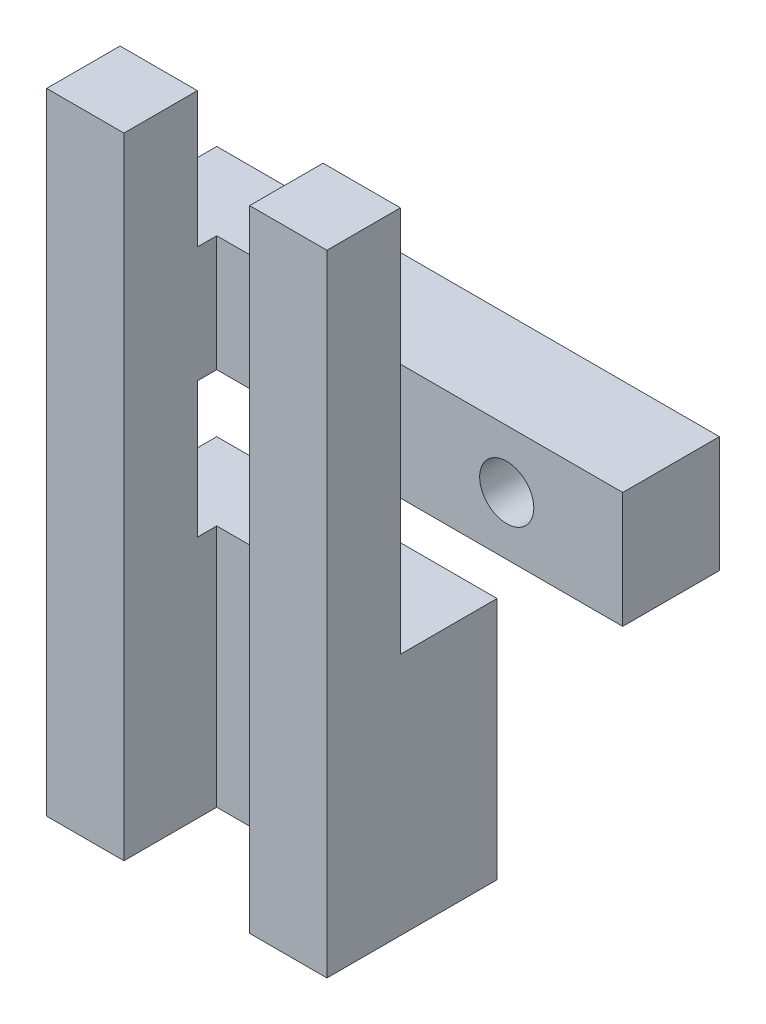
SolidWorks part; units mm, degrees
ref_plane "前视基准面" through (0, 0, 0) normal (0, 0, 1) x (1, 0, 0)
ref_plane "上视基准面" through (0, 0, 0) normal (0, 1, 0) x (1, 0, 0)
ref_plane "右视基准面" through (0, 0, 0) normal (1, 0, 0) x (0, 0, -1)
other "Configuration Table"
sketch "草图1" plane through (0, 0, 0) normal (0, 0, 1) x (1, 0, 0)
  line L1 (0, 0) -> (26, 0)
  line L2 (0, 0) -> (0, -6)
  line L3 (0, -6) -> (26, -6)
  line L4 (26, 0) -> (26, -6)
  circle A0 centre (20, -3) radius 1.4
  dimension "D5" = 2.8
  dimension "D1" = 26
  dimension "D2" = 6
  dimension "D3" = 3
  dimension "D4" = 6
extrude "凸台-拉伸1" add sketch "草图1" along normal blind 5
sketch "草图2" plane through (0, 0, 5) normal (0, 0, 1) x (1, 0, 0)
  line L0 (20, -3) -> (50020, -3) construction
  line L1 (-3.5767, 7) -> (49996.4233, 7) construction
  line L2 (0, 0) -> (0, -6) construction
  line L3 (0, 7) -> (4, 7)
  line L4 (0, 7) -> (0, -25.6)
  line L5 (0, -25.6) -> (4, -25.6)
  line L6 (4, 7) -> (4, -25.6)
  line L7 (10.5, 7) -> (14.5, 7)
  line L8 (10.5, 7) -> (10.5, -25.6)
  line L9 (10.5, -25.6) -> (14.5, -25.6)
  line L10 (14.5, 7) -> (14.5, -25.6)
  dimension "D1" = 10
  dimension "D2" = 32.6
  dimension "D3" = 4
  dimension "D4" = 6.5
  dimension "D5" = 4
extrude "凸台-拉伸2" add sketch "草图2" along normal blind 3.8
sketch "草图3" plane through (0, 0, 5) normal (0, 0, 1) x (1, 0, 0)
  line L5 (4, 0) -> (10.5, 0)
  line L6 (4, 0) -> (4, -6)
  line L7 (4, -6) -> (10.5, -6)
  line L8 (10.5, 0) -> (10.5, -6)
extrude "切除-拉伸1" cut sketch "草图3" against normal blind 1
sketch "草图4" plane through (0, 0, 5) normal (0, 0, -1) x (-1, 0, 0)
  line L0 (-20, -3) -> (49980, -3) construction
  line L1 (8.7575, -13) -> (-49991.2425, -13) construction
  line L2 (-14.5, -25.6) -> (-14.5, -6) construction
  line L3 (-14.5, -13) -> (0, -13)
  line L4 (-14.5, -13) -> (-14.5, -25.6)
  line L5 (-14.5, -25.6) -> (0, -25.6)
  line L6 (0, -13) -> (0, -25.6)
  dimension "D1" = 10
extrude "凸台-拉伸3" add sketch "草图4" along normal blind 5
sketch "草图5" plane through (0, 0, 5) normal (0, 0, 1) x (1, 0, 0)
  line L1 (4, -13) -> (10.5, -13)
  line L2 (4, -13) -> (4, -25.6)
  line L3 (4, -25.6) -> (10.5, -25.6)
  line L4 (10.5, -13) -> (10.5, -25.6)
extrude "切除-拉伸2" cut sketch "草图5" against normal blind 1
